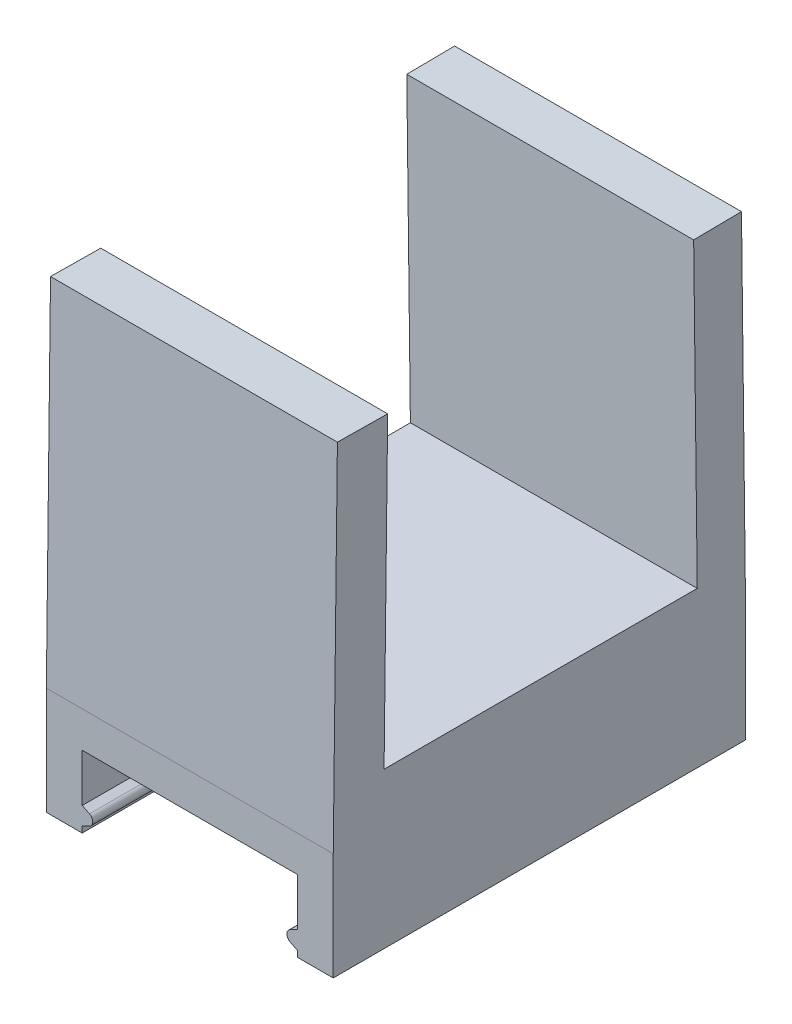
SolidWorks part; units mm, degrees
ref_plane "Front Plane" through (0, 0, 0) normal (0, 0, 1) x (1, 0, 0)
ref_plane "Top Plane" through (0, 0, 0) normal (0, 1, 0) x (1, 0, 0)
ref_plane "Right Plane" through (0, 0, 0) normal (1, 0, 0) x (0, 0, -1)
sketch "Sketch1" plane through (0, 0, 0) normal (0, 0, 1) x (1, 0, 0)
  line L1 (-9, 3) -> (9, 3)
  line L2 (-9, 3) -> (-9, -3)
  line L4 (9, 3) -> (9, -3)
  line L5 (-9, 3) -> (9, -3) construction
  line L6 (-9, -3) -> (9, 3) construction
  point P0 (0, 0)
  dimension "D1" = 6
  dimension "D2" = 18
sketch "Sketch2" plane through (0, 0, 0) normal (0, 0, 1) x (1, 0, 0)
  line L1 (-9, 3) -> (9, 3) construction
  line L2 (-9, 3) -> (-9, -3) construction
  line L3 (9, -1.75) -> (7.5, -1.75) construction
  line L4 (-9, 3) -> (9, 3)
  line L5 (-9, 3) -> (-9, -1)
  line L6 (-9, -2.5) -> (9, -2.5) construction
  line L7 (-9, -1.75) -> (-7.5, -1.75) construction
  line L8 (-9, -2.5) -> (-8.3944, -2.1972)
  line L9 (-9, -1) -> (-8.3944, -1.3028)
  line L10 (0, 0) -> (0, -5.5546) construction
  line L11 (-9, 3) -> (9, -3) construction
  line L12 (-9, -2.5) -> (-9, -3)
  line L13 (9, -2.5) -> (9, -3)
  line L14 (9, -1) -> (8.3944, -1.3028)
  line L15 (9, -2.5) -> (8.3944, -2.1972)
  line L16 (9, 3) -> (9, -1)
  line L17 (-9, -3) -> (-12, -3)
  line L18 (-12, -3) -> (-12, 6)
  line L19 (-12, 6) -> (12, 6)
  line L20 (12, 6) -> (12, -3)
  line L21 (12, -3) -> (9, -3)
  arc A0 (-8.3944, -1.3028) -> (-8.3944, -2.1972) centre (-8.618, -1.75) cw
  arc A1 (8.3944, -1.3028) -> (8.3944, -2.1972) centre (8.618, -1.75) ccw
  dimension "D4" = 0.5
  dimension "D1" = 0.5
  dimension "D2" = 1.5
  dimension "D3" = 1.5
  dimension "D5" = 3
extrude "Boss-Extrude1" add sketch "Sketch2" along normal blind 34.5
sketch "Sketch3" plane through (-12, 0, 0) normal (-1, 0, 0) x (0, 0, 1)
  line L0 (29.9475, 35.6) -> (30.2475, 10)
  line L1 (29.9475, 10) -> (4.3475, 10) construction
  line L2 (29.9475, 10) -> (29.9475, 35.6) construction
  line L3 (4.3475, 10) -> (4.3475, 35.4) construction
  line L4 (30.2475, 10) -> (4.0475, 10)
  line L5 (4.0475, 10) -> (4.3475, 35.4)
  line L6 (34.1525, 35.6493) -> (34.5, 6)
  line L7 (34.5, 6) -> (0, 6)
  line L8 (0, 6) -> (0.3478, 35.4472)
  line L9 (34.1525, 35.6493) -> (29.9475, 35.6)
  line L10 (4.3475, 35.4) -> (0.3478, 35.4472)
  point P10 (0, 0)
extrude "Boss-Extrude2" add sketch "Sketch3" against normal up to surface (24 mm away) up to face at (12, 1.5, 17.25)
